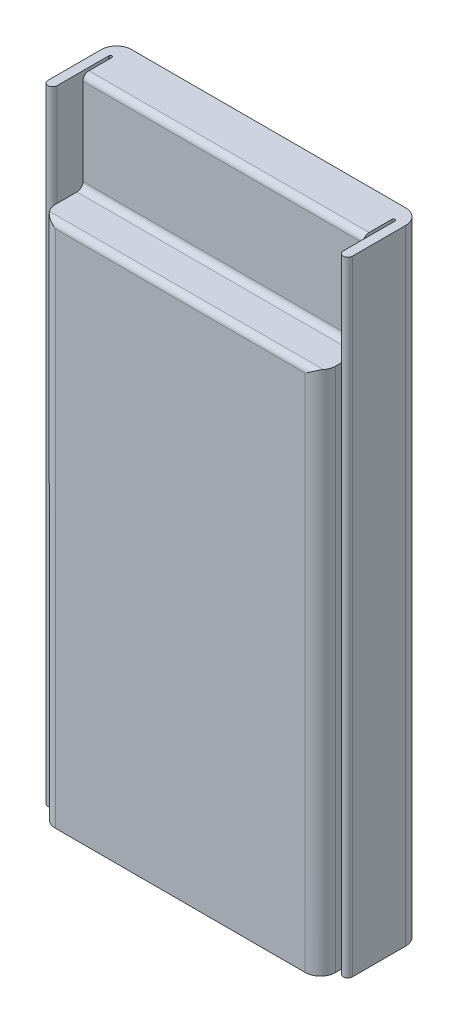
SolidWorks part; units mm, degrees
ref_plane "Front" through (0, 0, 0) normal (0, 0, 1) x (1, 0, 0)
ref_plane "Top" through (0, 0, 0) normal (0, 1, 0) x (1, 0, 0)
ref_plane "Right" through (0, 0, 0) normal (1, 0, 0) x (0, 0, -1)
sketch "Эскиз1" plane through (0, 0, 0) normal (0, 1, 0) x (1, 0, 0)
  line L0 (-9, 0) -> (9, 0)
  line L1 (-8.2, -5.8) -> (8.2, -5.8)
  line L2 (-10, -1) -> (-10, -4.5)
  line L3 (10, -1) -> (10, -4.5)
  line L4 (-9.2, -4.8) -> (-9.2, -1.1)
  line L5 (9.2, -1.1) -> (9.2, -4.8)
  line L6 (9.4, -4.5) -> (9.4, -1.1)
  line L7 (-9.4, -4.5) -> (-9.4, -1.1)
  arc A0 (-9, 0) -> (-10, -1) centre (-9, -1) ccw
  arc A1 (9, 0) -> (10, -1) centre (9, -1) cw
  arc A2 (-9.2, -4.8) -> (-8.2, -5.8) centre (-8.2, -4.8) ccw
  arc A3 (9.2, -4.8) -> (8.2, -5.8) centre (8.2, -4.8) cw
  arc A4 (10, -4.5) -> (9.4, -4.5) centre (9.7, -4.5) cw
  arc A5 (9.2, -1.1) -> (9.4, -1.1) centre (9.3, -1.1) cw
  arc A6 (-10, -4.5) -> (-9.4, -4.5) centre (-9.7, -4.5) ccw
  arc A7 (-9.2, -1.1) -> (-9.4, -1.1) centre (-9.3, -1.1) ccw
  point P20 (9.3, -1)
  point P21 (9.7, -4.8)
  point P27 (-9.3, -1)
  point P28 (-9.7, -4.8)
  dimension "D1" = 20
  dimension "D3" = 1
  dimension "D4" = 1
  dimension "D5" = 0.3
  dimension "D6" = 0.1
  dimension "D2" = 5.8
extrude "Бобышка-Вытянуть1" add sketch "Эскиз1" along normal mid plane 41
sketch "Эскиз2" plane through (0, 0, 0) normal (1, 0, 0) x (0, 0, -1)
  line L0 (-3, 20.1) -> (-3, 14.4)
  line L1 (-3.4, 14) -> (-5.4, 14)
  line L2 (-5.8, 20.5) -> (-5.8, 13.6)
  line L3 (-5.8, 20.5) -> (-5.8, -20.5) construction
  line L6 (-5.8, 20.5) -> (-2.6, 20.5)
  line L7 (0, 20.5) -> (-1, 20.5) construction
  arc A0 (-3, 14.4) -> (-3.4, 14) centre (-3.4, 14.4) cw
  arc A1 (-5.4, 14) -> (-5.8, 13.6) centre (-5.4, 13.6) ccw
  arc A2 (-2.6, 20.5) -> (-3, 20.1) centre (-2.6, 20.1) ccw
  dimension "D1" = 0.4
  dimension "D2" = 3
  dimension "D3" = 6.5
extrude "Вырез-Вытянуть1" cut sketch "Эскиз2" against normal up to next and the other way up to next
